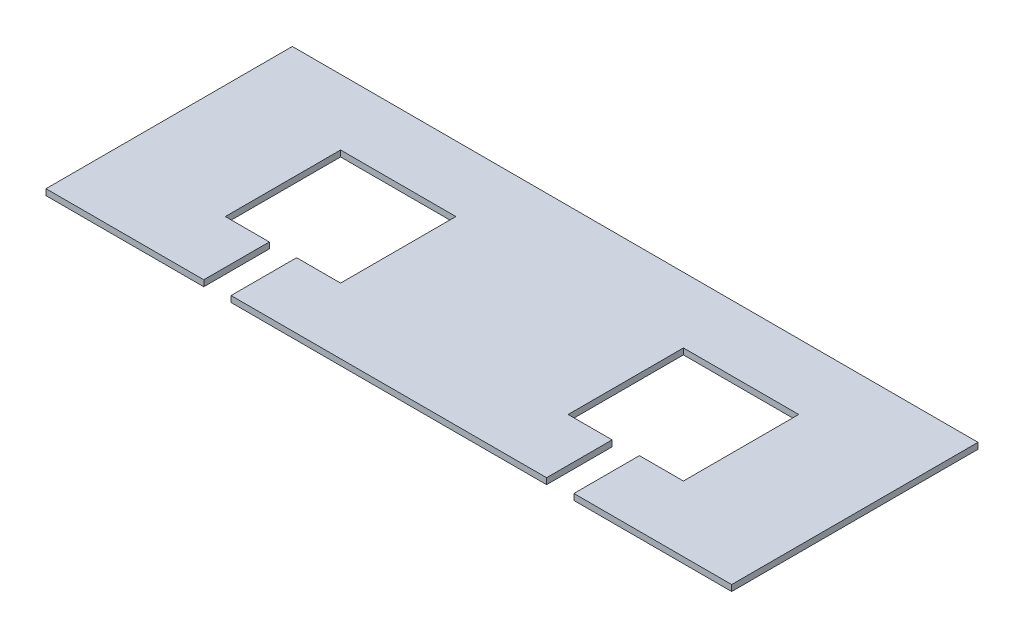
SolidWorks part; units mm, degrees
material "Copper"
ref_plane "Front Plane" through (0, 0, 0) normal (0, 0, 1) x (1, 0, 0)
ref_plane "Top Plane" through (0, 0, 0) normal (0, 1, 0) x (1, 0, 0)
ref_plane "Right Plane" through (0, 0, 0) normal (1, 0, 0) x (0, 0, -1)
sketch "Sketch1" plane through (0, 0, 0) normal (0, 1, 0) x (1, 0, 0)
  line L1 (0, 0) -> (113, 0)
  line L2 (0, 0) -> (0, 40.6)
  line L3 (0, 40.6) -> (113, 40.6)
  line L4 (113, 0) -> (113, 40.6)
extrude "Boss-Extrude1" add sketch "Sketch1" along normal blind 1
ref_plane "Plane1" through (56.5, 0, 0) normal (-1, 0, 0) x (0, 0, 1)
ref_plane "Plane2" through (0, 0, -20.3) normal (0, 0, -1) x (-1, 0, 0)
ref_plane "Plane3" through (84.75, 0, 0) normal (-1, 0, 0) x (0, 0, 1)
ref_plane "Plane4" through (28.25, 0, 0) normal (-1, 0, 0) x (0, 0, 1)
sketch "Sketch2" plane through (0, 1, 0) normal (0, 1, 0) x (1, 0, 0)
  line L0 (28.25, 6.6115) -> (28.25, -6.6115) construction
  line L1 (37.75, 10.8) -> (30.5, 10.8)
  line L2 (37.75, 10.8) -> (37.75, 29.8)
  line L3 (37.75, 29.8) -> (18.75, 29.8)
  line L4 (18.75, 10.8) -> (18.75, 29.8)
  line L5 (37.75, 10.8) -> (18.75, 29.8) construction
  line L6 (37.75, 29.8) -> (18.75, 10.8) construction
  line L7 (10.3343, 20.3) -> (-10.3343, 20.3) construction
  line L8 (26, 10.8) -> (26, 0)
  line L9 (0, 0) -> (113, 0) construction
  line L10 (30.5, 10.8) -> (30.5, 0)
  line L11 (26, 0) -> (30.5, 0)
  line L12 (26, 10.8) -> (18.75, 10.8)
  point P0 (28.25, 20.3)
  dimension "D1" = 19
  dimension "D2" = 19
  dimension "D3" = 4.5
extrude "Cut-Extrude1" cut sketch "Sketch2" against normal through all
mirror "Mirror1" about plane through (56.5, 0, 0) normal (-1, 0, 0) of "Cut-Extrude1"
